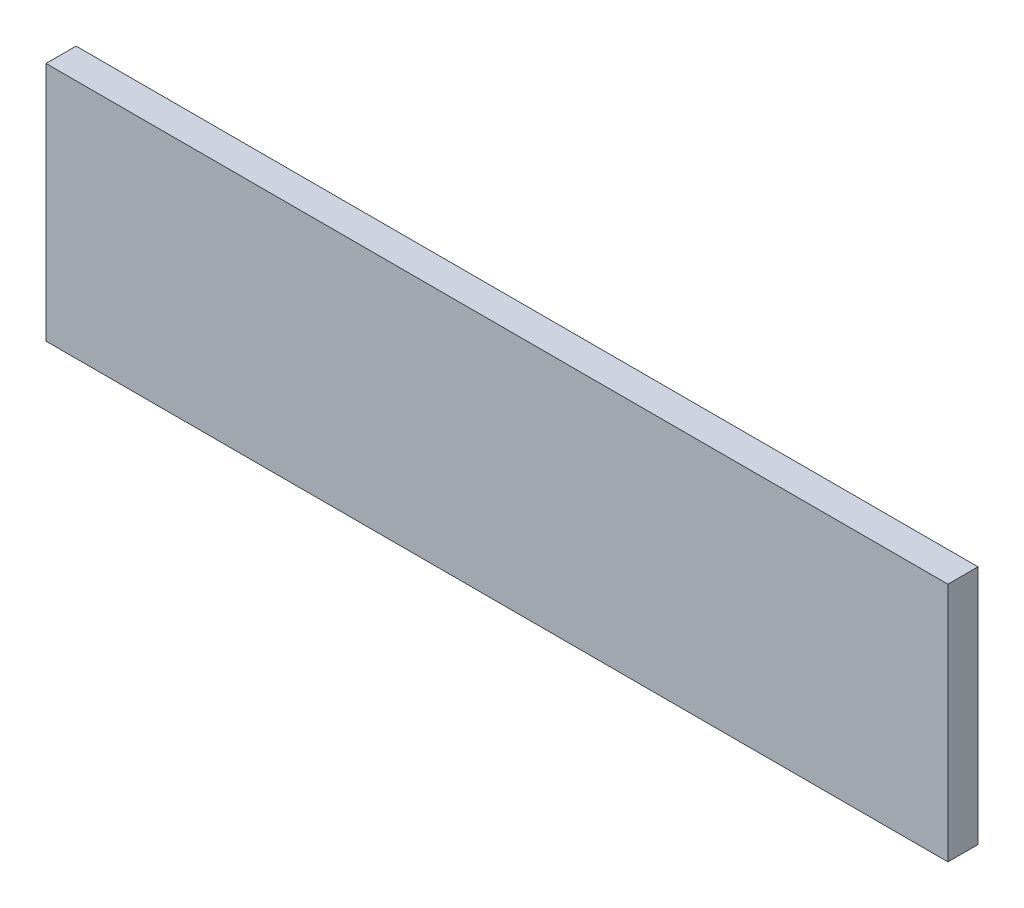
SolidWorks part; units mm, degrees
material "Maple"
ref_plane "Front Plane" through (0, 0, 0) normal (0, 0, 1) x (1, 0, 0)
ref_plane "Top Plane" through (0, 0, 0) normal (0, 1, 0) x (1, 0, 0)
ref_plane "Right Plane" through (0, 0, 0) normal (1, 0, 0) x (0, 0, -1)
sketch "Sketch1" plane through (0, 0, 0) normal (0, 0, 1) x (1, 0, 0)
  line L1 (150, 40) -> (-150, 40)
  line L2 (150, 40) -> (150, -40)
  line L3 (150, -40) -> (-150, -40)
  line L4 (-150, 40) -> (-150, -40)
  line L5 (150, 40) -> (-150, -40) construction
  line L6 (150, -40) -> (-150, 40) construction
  point P0 (0, 0)
  dimension "D1" = 300
  dimension "D2" = 80
extrude "Boss-Extrude1" add sketch "Sketch1" along normal blind 10
